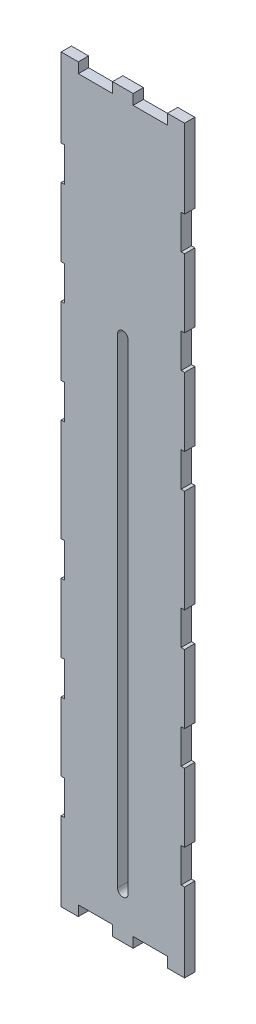
SolidWorks part; units mm, degrees
material "Acrylic (Medium-high impact)"
ref_plane "Front Plane" through (0, 0, 0) normal (0, 0, 1) x (1, 0, 0)
ref_plane "Top Plane" through (0, 0, 0) normal (0, 1, 0) x (1, 0, 0)
ref_plane "Right Plane" through (0, 0, 0) normal (1, 0, 0) x (0, 0, -1)
sketch "Sketch1" plane through (0, 0, 0) normal (0, 0, 1) x (1, 0, 0)
  line L0 (0, 105) -> (34, 105) construction
  line L1 (0, 0) -> (34, 0)
  line L2 (0, 0) -> (0, 210)
  line L3 (0, 210) -> (34, 210)
  line L4 (34, 0) -> (34, 210)
  line L13 (17, 210) -> (17, 0) construction
  line L34 (34, 50) -> (35, 50)
  line L35 (34, 50) -> (34, 60)
  line L36 (34, 60) -> (35, 60)
  line L37 (35, 50) -> (35, 60)
  line L38 (34, 80) -> (35, 80)
  line L39 (34, 80) -> (34, 90)
  line L40 (34, 90) -> (35, 90)
  line L41 (35, 80) -> (35, 90)
  line L42 (34, 20) -> (35, 20)
  line L43 (34, 20) -> (34, 30)
  line L44 (34, 30) -> (35, 30)
  line L45 (35, 20) -> (35, 30)
  line L46 (35, 210) -> (35, 0)
  line L47 (35, 0) -> (34, 0)
  line L48 (35, 210) -> (34, 210)
  line L49 (34, 180) -> (35, 180)
  line L50 (35, 190) -> (35, 180)
  line L51 (34, 190) -> (35, 190)
  line L52 (34, 190) -> (34, 180)
  line L53 (34, 150) -> (35, 150)
  line L54 (35, 160) -> (35, 150)
  line L55 (34, 160) -> (35, 160)
  line L56 (34, 160) -> (34, 150)
  line L57 (34, 120) -> (35, 120)
  line L58 (35, 130) -> (35, 120)
  line L59 (34, 130) -> (35, 130)
  line L60 (34, 130) -> (34, 120)
  line L61 (-1, 210) -> (0, 210)
  line L62 (-1, 0) -> (0, 0)
  line L63 (-1, 210) -> (-1, 0)
  line L64 (0, 30) -> (-1, 30)
  line L65 (-1, 20) -> (-1, 30)
  line L66 (0, 20) -> (-1, 20)
  line L67 (0, 20) -> (0, 30)
  line L68 (0, 60) -> (-1, 60)
  line L69 (-1, 50) -> (-1, 60)
  line L70 (0, 50) -> (-1, 50)
  line L71 (0, 50) -> (0, 60)
  line L72 (0, 90) -> (-1, 90)
  line L73 (-1, 80) -> (-1, 90)
  line L74 (0, 80) -> (-1, 80)
  line L75 (0, 80) -> (0, 90)
  line L76 (0, 130) -> (0, 120)
  line L77 (0, 130) -> (-1, 130)
  line L78 (-1, 130) -> (-1, 120)
  line L79 (0, 120) -> (-1, 120)
  line L80 (0, 160) -> (0, 150)
  line L81 (0, 160) -> (-1, 160)
  line L82 (-1, 160) -> (-1, 150)
  line L83 (0, 150) -> (-1, 150)
  line L84 (0, 190) -> (0, 180)
  line L85 (0, 190) -> (-1, 190)
  line L86 (-1, 190) -> (-1, 180)
  line L87 (0, 180) -> (-1, 180)
  line L88 (-1, 210) -> (-1, 213)
  line L89 (4, 210) -> (14, 210)
  line L90 (4, 210) -> (4, 213)
  line L91 (4, 213) -> (14, 213)
  line L92 (14, 210) -> (14, 213)
  line L93 (20, 210) -> (30, 210)
  line L94 (20, 210) -> (20, 213)
  line L95 (20, 213) -> (30, 213)
  line L96 (30, 210) -> (30, 213)
  line L97 (-1, 213) -> (35, 213)
  line L98 (35, 210) -> (35, 213)
  line L99 (4, -3) -> (14, -3)
  line L100 (14, 0) -> (14, -3)
  line L101 (4, 0) -> (14, 0)
  line L102 (4, 0) -> (4, -3)
  line L103 (20, -3) -> (30, -3)
  line L104 (30, 0) -> (30, -3)
  line L105 (20, 0) -> (30, 0)
  line L106 (20, 0) -> (20, -3)
  line L107 (-1, -3) -> (-1, 0)
  line L108 (-1, -3) -> (35, -3)
  line L109 (35, -3) -> (35, 0)
  dimension "D1" = 210
  dimension "D2" = 34
  dimension "D3" = 1
  dimension "D4" = 10
  dimension "D5" = 20
  dimension "D6" = 20
  dimension "D7" = 20
  dimension "D8" = 10
  dimension "D9" = 3
  dimension "D10" = 5
  dimension "D11" = 5
extrude "Boss-Extrude1" add sketch "Sketch1" along normal blind 3
sketch "Sketch2" plane through (0, 0, 3) normal (0, 0, 1) x (1, 0, 0)
  line L0 (17, 150) -> (17, 10) construction
  line L1 (18.55, 150) -> (18.55, 10)
  line L2 (15.45, 150) -> (15.45, 10)
  line L4 (4, 210) -> (14, 210) construction
  arc A0 (18.55, 150) -> (15.45, 150) centre (17, 150) ccw
  arc A1 (15.45, 10) -> (18.55, 10) centre (17, 10) ccw
  point P2 (17, 80)
  dimension "D1" = 3.1
  dimension "D2" = 10
  dimension "D3" = 60
  dimension "D4" = 17
extrude "Cut-Extrude1" cut sketch "Sketch2" against normal through all
